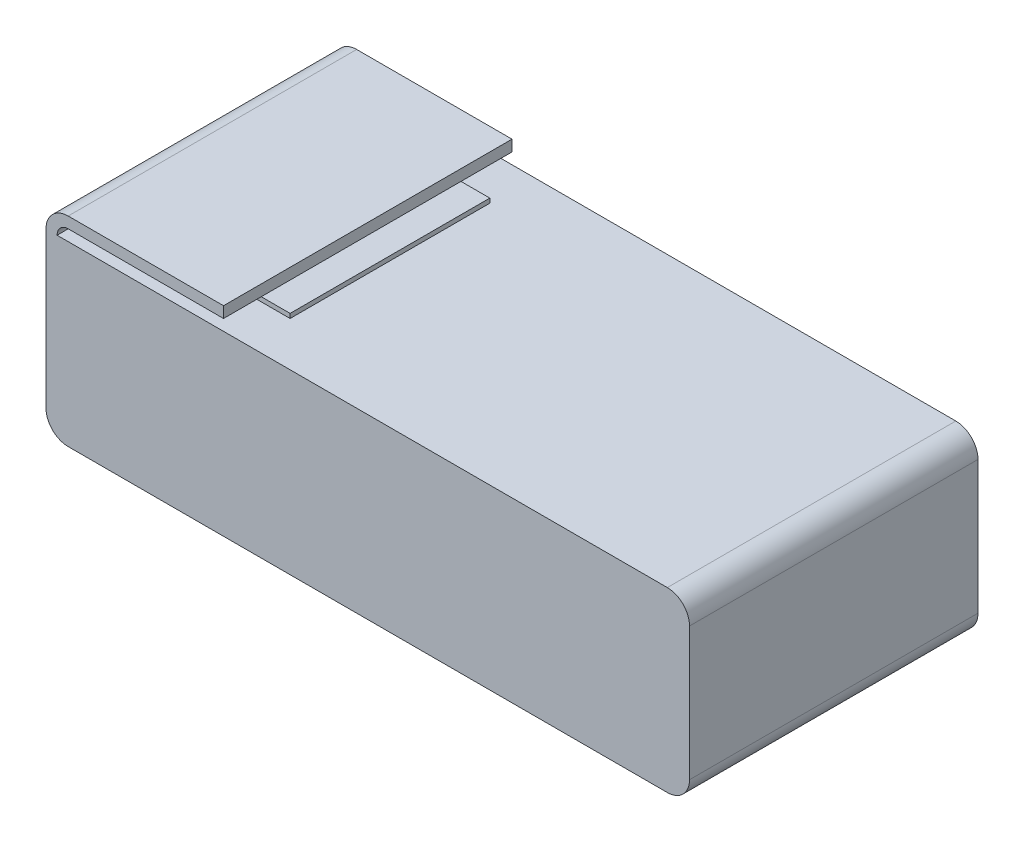
SolidWorks part; units mm, degrees
ref_plane "Front" through (0, 0, 0) normal (0, 0, 1) x (1, 0, 0)
ref_plane "Top" through (0, 0, 0) normal (0, 1, 0) x (1, 0, 0)
ref_plane "Right" through (0, 0, 0) normal (1, 0, 0) x (0, 0, -1)
sketch "Sketch1" plane through (0, 0, 0) normal (0, 0, 1) x (1, 0, 0)
  line L0 (5, 0) -> (140, 0)
  line L1 (145, 5) -> (145, 35)
  line L2 (0, 5) -> (0, 40)
  line L3 (5, 45) -> (40, 45)
  line L4 (140, 40) -> (10, 40)
  line L5 (5, 42.5) -> (40, 42.5)
  line L6 (2.5, 5) -> (2.5, 40)
  line L7 (5, 2.5) -> (140, 2.5)
  line L8 (142.5, 5) -> (142.5, 35)
  line L9 (140, 37.5) -> (10, 37.5)
  line L10 (40, 45) -> (40, 42.5)
  line L11 (10, 40) -> (10, 37.5)
  arc A0 (145, 35) -> (140, 40) centre (140, 35) ccw
  arc A1 (140, 0) -> (145, 5) centre (140, 5) ccw
  arc A2 (5, 0) -> (0, 5) centre (5, 5) cw
  arc A3 (0, 40) -> (5, 45) centre (5, 40) cw
  arc A4 (2.5, 40) -> (5, 42.5) centre (5, 40) cw
  arc A5 (5, 2.5) -> (2.5, 5) centre (5, 5) cw
  arc A6 (140, 2.5) -> (142.5, 5) centre (140, 5) ccw
  arc A7 (142.5, 35) -> (140, 37.5) centre (140, 35) ccw
  point P9 (145, 40)
  point P12 (145, 0)
  point P15 (0, 0)
  point P18 (0, 45)
  dimension "D6" = 5
  dimension "D1" = 145
  dimension "D2" = 40
  dimension "D3" = 45
  dimension "D4" = 40
  dimension "D5" = 135
  dimension "D7" = 2.5
extrude "Boss-Extrude1" add sketch "Sketch1" along normal mid plane 65 contours L3 L10 L5 A4 L6 A5 L7 A6 L8 A7 L9 L11 L4 A0 L1 A1 L0 A2 L2 A3
sketch "Sketch2" plane through (0, 0, 32.5) normal (0, 0, 1) x (1, 0, 0)
  line L12 (0, 40) -> (0, 5)
  line L13 (5, 0) -> (140, 0)
  line L14 (145, 5) -> (145, 35)
  line L15 (140, 40) -> (10, 40)
  line L16 (10, 40) -> (10, 37.5)
  line L17 (10, 37.5) -> (140, 37.5)
  line L18 (142.5, 35) -> (142.5, 5)
  line L19 (140, 2.5) -> (5, 2.5)
  line L20 (2.5, 5) -> (2.5, 40)
  line L21 (5, 42.5) -> (40, 42.5)
  line L22 (40, 42.5) -> (40, 45)
  line L23 (40, 45) -> (5, 45)
  line L24 (0, 40) -> (0, 5)
  line L25 (5, 0) -> (140, 0)
  line L26 (145, 5) -> (145, 35)
  line L27 (140, 40) -> (0, 40)
  arc A8 (5, 45) -> (0, 40) centre (5, 40) ccw
  arc A9 (0, 5) -> (5, 0) centre (5, 5) ccw
  arc A10 (140, 0) -> (145, 5) centre (140, 5) ccw
  arc A11 (145, 35) -> (140, 40) centre (140, 35) ccw
  arc A12 (142.5, 35) -> (140, 37.5) centre (140, 35) ccw
  arc A13 (140, 2.5) -> (142.5, 5) centre (140, 5) ccw
  arc A14 (2.5, 5) -> (5, 2.5) centre (5, 5) ccw
  arc A15 (5, 42.5) -> (2.5, 40) centre (5, 40) ccw
  arc A17 (0, 5) -> (5, 0) centre (5, 5) ccw
  arc A18 (140, 0) -> (145, 5) centre (140, 5) ccw
  arc A19 (145, 35) -> (140, 40) centre (140, 35) ccw
  dimension "D1" = 0
extrude "Boss-Extrude2" add sketch "Sketch2" against normal blind 2.5 contours L25 A18 L26 A19 L27 L24 A17
mirror "Mirror1" about plane through (0, 0, 0) normal (0, 0, 1) of "Boss-Extrude2"
sketch "Sketch3" plane through (0, 40, 0) normal (0, 1, 0) x (1, 0, 0)
  line L0 (5, -32.5) -> (40, -32.5) construction
  line L1 (30, -22.5) -> (45, -22.5)
  line L2 (30, -22.5) -> (30, 22.5)
  line L3 (30, 22.5) -> (45, 22.5)
  line L4 (45, -22.5) -> (45, 22.5)
  line L6 (40, -32.5) -> (40, 32.5) construction
  line L7 (5, 32.5) -> (40, 32.5) construction
  dimension "D1" = 10
  dimension "D2" = 5
  dimension "D3" = 10
  dimension "D4" = 10
extrude "Boss-Extrude3" add sketch "Sketch3" along normal blind 1
sketch "Sketch4" plane through (0, 0, 0) normal (0, -1, 0) x (1, 0, 0)
  line L0 (5, 32.5) -> (140, 32.5) construction
  line L1 (10, -27.5) -> (35, -27.5)
  line L2 (10, -27.5) -> (10, 27.5)
  line L3 (10, 27.5) -> (35, 27.5)
  line L4 (35, -27.5) -> (35, 27.5)
  line L6 (5, 32.5) -> (5, -32.5) construction
  line L7 (110, -27.5) -> (135, -27.5)
  line L8 (110, -27.5) -> (110, 27.5)
  line L9 (110, 27.5) -> (135, 27.5)
  line L10 (135, -27.5) -> (135, 27.5)
  dimension "D1" = 55
  dimension "D2" = 5
  dimension "D3" = 55
  dimension "D4" = 25
  dimension "D5" = 25
  dimension "D6" = 5
  dimension "D7" = 75
  dimension "D8" = 5
extrude "Boss-Extrude4" add sketch "Sketch4" along normal blind 1
